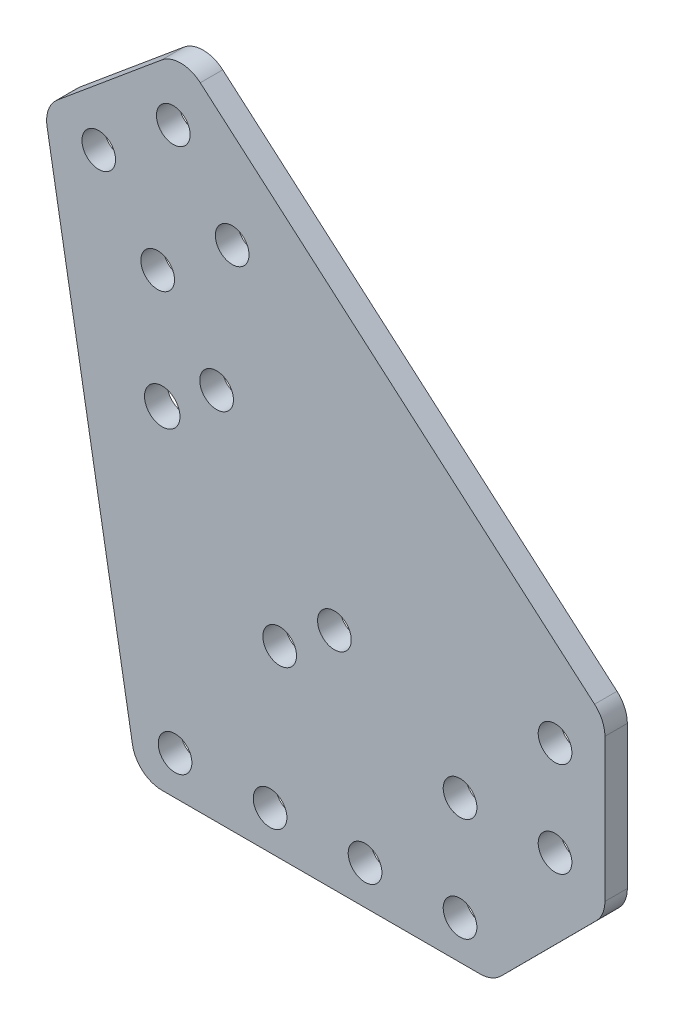
SolidWorks part; units mm, degrees
ref_plane "前视基准面" through (0, 0, 0) normal (0, 0, 1) x (1, 0, 0)
ref_plane "上视基准面" through (0, 0, 0) normal (0, 1, 0) x (1, 0, 0)
ref_plane "右视基准面" through (0, 0, 0) normal (1, 0, 0) x (0, 0, -1)
sketch "草图2" plane through (0, 0, 0) normal (0, 0, 1) x (1, 0, 0)
  line L3 (-167.5908, -24.568) -> (-179.9848, 46.8859)
  line L5 (-179.9848, 46.8859) -> (-161.6694, 62.1355)
  line L6 (-161.6694, 62.1355) -> (-105.0104, 13.1216)
  line L8 (-105.0104, 13.1216) -> (-105.0104, -9.4804)
  line L11 (-105.0104, -9.4804) -> (-120.0538, -24.568)
  line L12 (-120.0538, -24.568) -> (-167.5908, -24.568)
  circle A4 centre (-154.837, 43.2532) radius 2.25
  circle A5 centre (-164.7999, 35.3773) radius 2.25
  circle A6 centre (-162.7129, 53.2161) radius 2.25
  circle A7 centre (-172.6758, 45.3402) radius 2.25
  circle A8 centre (-111.6769, 7.182) radius 2.25
  circle A14 centre (-124.3769, -5.518) radius 2.25
  circle A28 centre (-124.3769, -19.3864) radius 2.25
  circle A29 centre (-137.0769, -19.3864) radius 2.25
  circle A30 centre (-149.7769, -19.3864) radius 2.25
  circle A31 centre (-162.4769, -19.3864) radius 2.25
  circle A33 centre (-175.1769, -19.3864) radius 2.25 [skipped]
  circle A35 centre (-141.1722, 5.4885) radius 2.25
  circle A36 centre (-148.4897, 0) radius 2.25
  circle A38 centre (-156.924, 25.4143) radius 2.25
  circle A39 centre (-164.19, 19.9017) radius 2.3683
  circle A40 centre (-111.6769, -5.518) radius 2.25
  dimension "D4" = 5
  dimension "D5" = 4.5
  dimension "D6" = 4.5
  dimension "D7" = 4.5
extrude "凸台-拉伸2" add sketch "草图2" along normal blind 3
fillet "圆角2" radius 4 6 edges at (-120.0538, -24.568, 1.5) (-167.5908, -24.568, 1.5) (-179.9848, 46.8859, 1.5) (-161.6694, 62.1355, 1.5) (-105.0104, -9.4804, 1.5) (-105.0104, 13.1216, 1.5)
